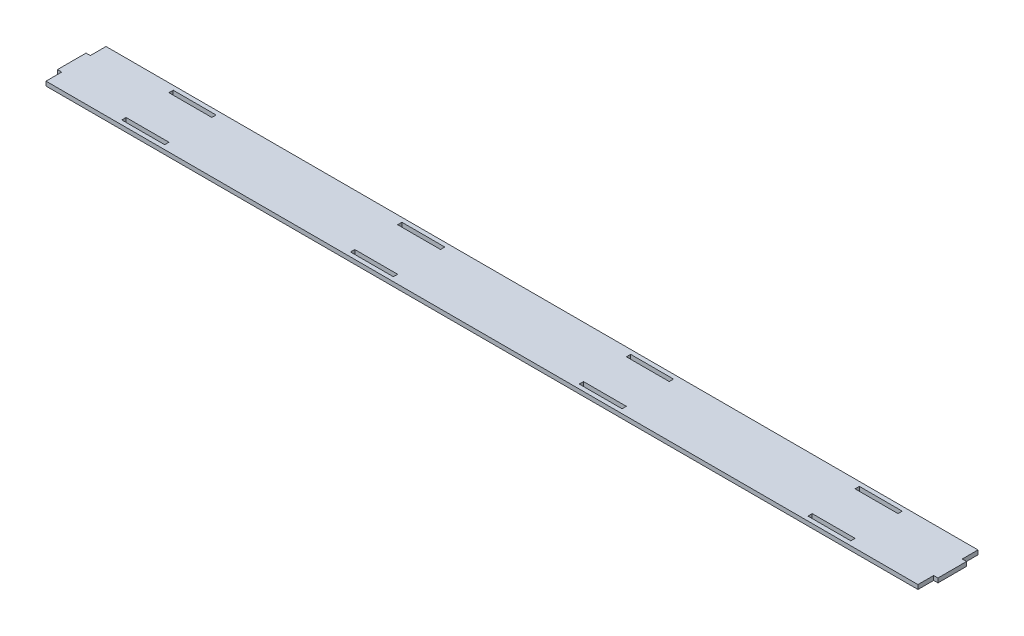
SolidWorks part; units mm, degrees
material "ABS"
ref_plane "Front Plane" through (0, 0, 0) normal (0, 0, 1) x (1, 0, 0)
ref_plane "Top Plane" through (0, 0, 0) normal (0, 1, 0) x (1, 0, 0)
ref_plane "Right Plane" through (0, 0, 0) normal (1, 0, 0) x (0, 0, -1)
sketch "Sketch1" plane through (0, 0, 0) normal (0, 1, 0) x (1, 0, 0)
  line L0 (0, 21) -> (215.732, 21) construction
  line L1 (0, 0) -> (610, 0)
  line L2 (0, 0) -> (0, 11)
  line L3 (0, 42) -> (610, 42)
  line L4 (610, 0) -> (610, 11)
  line L5 (50, 6) -> (80, 6)
  line L6 (50, 6) -> (50, 3)
  line L7 (50, 3) -> (80, 3)
  line L8 (80, 6) -> (80, 3)
  line L9 (210, 6) -> (240, 6)
  line L10 (210, 6) -> (210, 3)
  line L11 (210, 3) -> (240, 3)
  line L12 (240, 6) -> (240, 3)
  line L13 (370, 6) -> (400, 6)
  line L14 (370, 6) -> (370, 3)
  line L15 (370, 3) -> (400, 3)
  line L16 (400, 6) -> (400, 3)
  line L17 (530, 6) -> (560, 6)
  line L18 (530, 6) -> (530, 3)
  line L19 (530, 3) -> (560, 3)
  line L20 (560, 6) -> (560, 3)
  line L21 (560, 36) -> (560, 39)
  line L22 (530, 39) -> (560, 39)
  line L23 (530, 36) -> (530, 39)
  line L24 (530, 36) -> (560, 36)
  line L25 (400, 36) -> (400, 39)
  line L26 (370, 39) -> (400, 39)
  line L27 (370, 36) -> (370, 39)
  line L28 (370, 36) -> (400, 36)
  line L29 (240, 36) -> (240, 39)
  line L30 (210, 39) -> (240, 39)
  line L31 (210, 36) -> (240, 36)
  line L32 (50, 39) -> (80, 39)
  line L33 (50, 36) -> (50, 39)
  line L34 (50, 36) -> (80, 36)
  line L35 (0, 0) -> (610, 0)
  line L36 (0, 42) -> (610, 42)
  line L37 (305, 42) -> (305, 11) construction
  line L38 (0, 31) -> (-3, 31)
  line L40 (0, 11) -> (-3, 11)
  line L41 (-3, 31) -> (-3, 11)
  line L42 (610, 11) -> (613, 11)
  line L43 (613, 31) -> (613, 11)
  line L44 (610, 31) -> (613, 31)
  line L45 (0, 31) -> (0, 42)
  line L46 (610, 31) -> (610, 42)
  line L47 (80, 39) -> (80, 36)
  line L48 (210, 39) -> (210, 36)
  point P35 (80, 36)
  dimension "D1" = 610
  dimension "D2" = 42
  dimension "D3" = 30
  dimension "D4" = 3
  dimension "D5" = 3
  dimension "D6" = 50
  dimension "D7" = 130
  dimension "D8" = 30
  dimension "D9" = 3
  dimension "D10" = 3
  dimension "D11" = 130
  dimension "D12" = 30
  dimension "D13" = 3
  dimension "D14" = 3
  dimension "D15" = 130
  dimension "D16" = 30
  dimension "D17" = 3
  dimension "D18" = 3
  dimension "D19" = 20
  dimension "D20" = 3
  dimension "D21" = 11
extrude "Boss-Extrude1" add sketch "Sketch1" along normal blind 3
